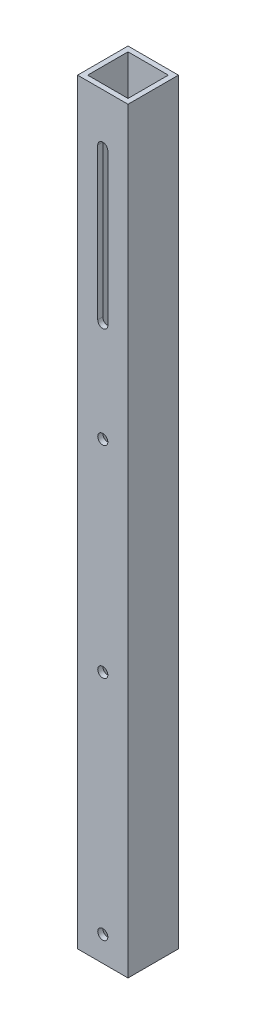
SolidWorks part; units mm, degrees
ref_plane "前视基准面" through (0, 0, 0) normal (0, 0, 1) x (1, 0, 0)
ref_plane "上视基准面" through (0, 0, 0) normal (0, 1, 0) x (1, 0, 0)
ref_plane "右视基准面" through (0, 0, 0) normal (1, 0, 0) x (0, 0, -1)
sketch "草图1" plane through (0, 0, 0) normal (0, 1, 0) x (1, 0, 0)
  line L1 (0, 0) -> (10, 0)
  line L2 (0, 0) -> (0, 10)
  line L3 (0, 10) -> (10, 10)
  line L4 (10, 0) -> (10, 10)
  line L5 (2, 2) -> (8, 2)
  line L6 (2, 2) -> (2, 8)
  line L7 (2, 8) -> (8, 8)
  line L8 (8, 2) -> (8, 8)
  point P5 (2, 2)
extrude "凸台-拉伸1" add sketch "草图1" along normal blind 150
sketch "草图2" plane through (0, 0, 0) normal (0, 0, 1) x (1, 0, 0)
  line L0 (4, 110) -> (4, 140)
  line L1 (4, 140) -> (6, 140)
  line L2 (6, 110) -> (6, 140)
  circle A0 centre (5, 140) radius 1
  circle A1 centre (5, 110) radius 1
  point P0 (5, 140)
  point P1 (5, 110)
extrude "切除-拉伸1" cut sketch "草图2" against normal blind 10 contours A1 L2 A0 L0 | A1 | L1 A0 | L1 A0
sketch "草图3" plane through (0, 0, 0) normal (0, 0, 1) x (1, 0, 0)
  circle A0 centre (5, 90) radius 1
  point P0 (5, 90)
extrude "切除-拉伸2" cut sketch "草图3" against normal blind 10
sketch "草图4" plane through (0, 0, -10) normal (0, 0, -1) x (-1, 0, 0)
  circle A0 centre (-5, 5) radius 1
  point P0 (-5, 5)
extrude "切除-拉伸3" cut sketch "草图4" against normal blind 10
sketch "草图5" plane through (0, 0, 0) normal (0, 1, 0) x (1, 0, 0)
  line L0 (1, 5) -> (1, 9)
  line L1 (1, 9) -> (9, 9)
  line L2 (9, 9) -> (9, 1)
  line L3 (9, 1) -> (1, 1)
  line L4 (1, 1) -> (1, 5)
  circle A0 centre (5, 5) radius 4
  point P0 (5, 5)
extrude "切除-拉伸4" cut sketch "草图5" along normal blind 150 contours A0 L1 L0 | A0 | A0 L4 L3 | A0 L2 L1 | A0 L3 L2
sketch "草图6" plane through (0, 0, -10) normal (0, 0, -1) x (-1, 0, 0)
  circle A0 centre (-5, 50) radius 1
  point P0 (-5, 50)
extrude "切除-拉伸5" cut sketch "草图6" against normal blind 10
